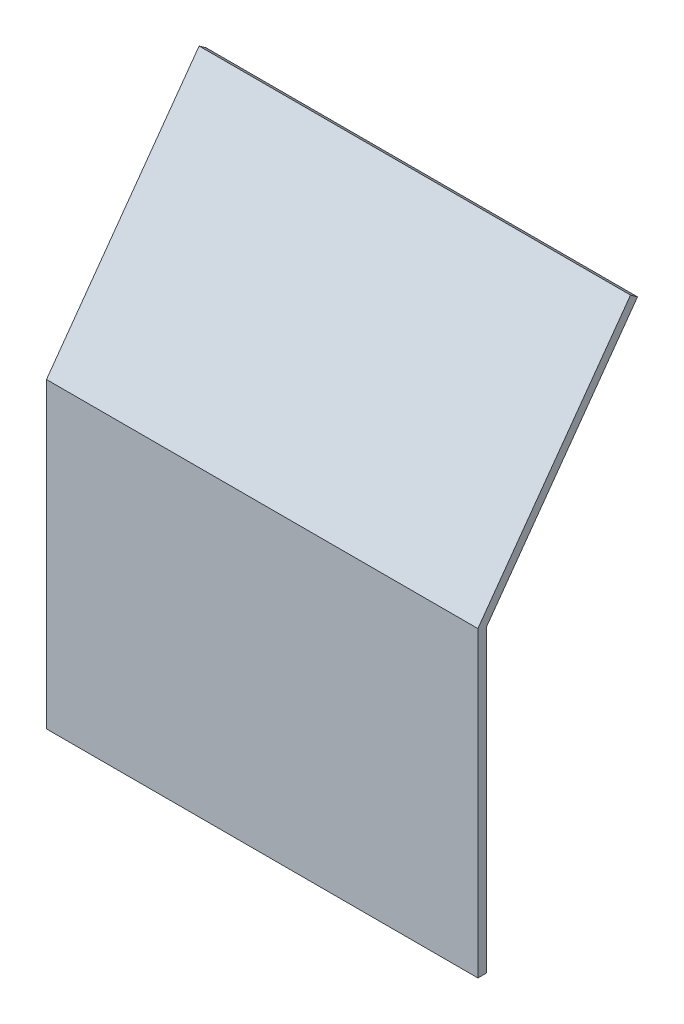
SolidWorks part; units mm, degrees
ref_plane "Front Plane" through (0, 0, 0) normal (0, 0, 1) x (1, 0, 0)
ref_plane "Top Plane" through (0, 0, 0) normal (0, 1, 0) x (1, 0, 0)
ref_plane "Right Plane" through (0, 0, 0) normal (1, 0, 0) x (0, 0, -1)
sketch "Sketch1" plane through (0, 0, 0) normal (1, 0, 0) x (0, 0, -1)
  line L0 (-4, 0) -> (-4, 140.2875)
  line L1 (-4, 140.2875) -> (66.7511, 238.8013)
  line L2 (66.7511, 238.8013) -> (70, 236.4679)
  line L3 (70, 236.4679) -> (0, 139)
  line L4 (0, 139) -> (0, 0)
  line L5 (0, 0) -> (-4, 0)
  line L6 (0, 0) -> (70, 0) construction
  line L7 (70, 0) -> (70, 236.4679) construction
  dimension "D1" = 4
  dimension "D2" = 120
  dimension "D3" = 139
  dimension "D4" = 70
extrude "Boss-Extrude1" add sketch "Sketch1" along normal mid plane 200
